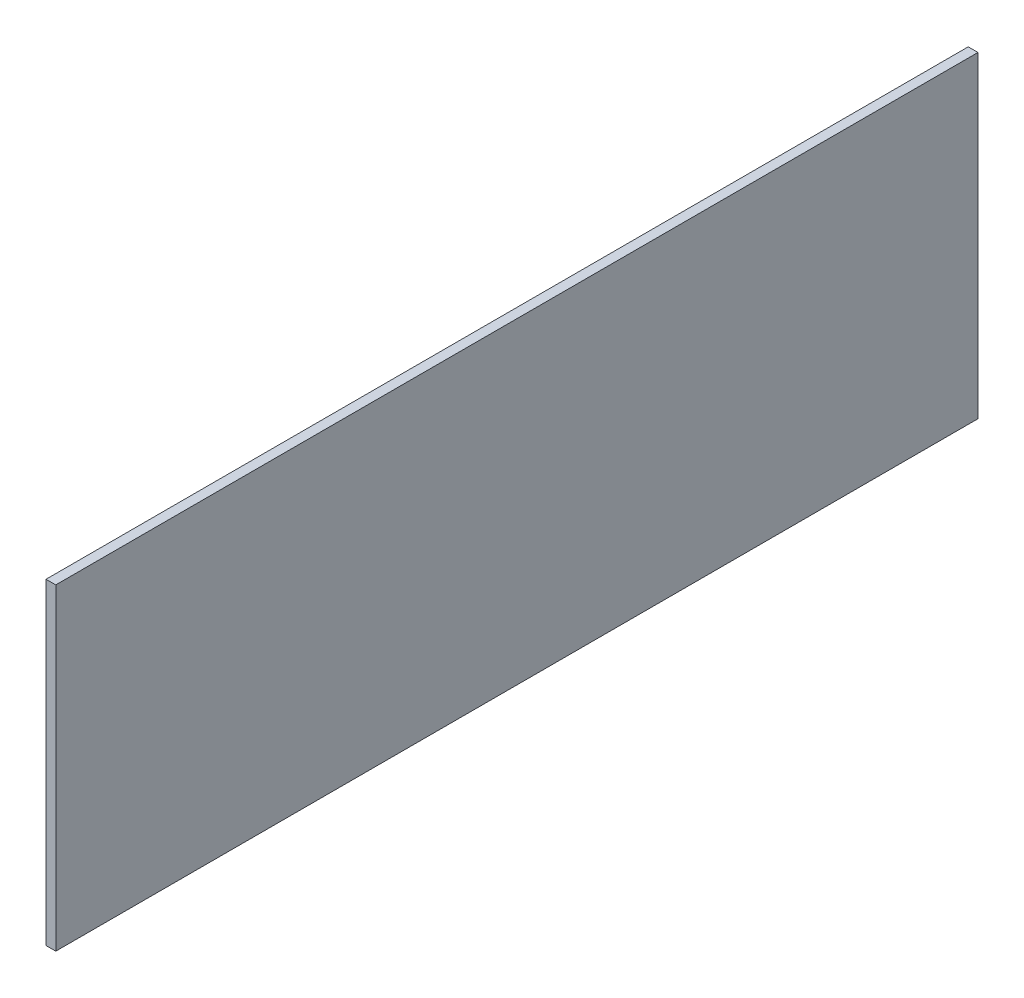
SolidWorks part; units mm, degrees
ref_plane "Front Plane" through (0, 0, 0) normal (0, 0, 1) x (1, 0, 0)
ref_plane "Top Plane" through (0, 0, 0) normal (0, 1, 0) x (1, 0, 0)
ref_plane "Right Plane" through (0, 0, 0) normal (1, 0, 0) x (0, 0, -1)
sketch "Sketch1" plane through (0, 0, 0) normal (0, 0, 1) x (1, 0, 0)
  line L0 (7463.6071, 3575.0777) -> (7463.6071, 3537.9447)
  line L1 (7463.6071, 3575.0777) -> (7462.4641, 3575.0777)
  line L2 (7463.6071, 3537.9447) -> (7462.4641, 3537.9447)
  line L3 (7462.4641, 3575.0777) -> (7462.4641, 3537.9447)
extrude "Boss-Extrude1" add sketch "Sketch1" along normal blind 107.95
